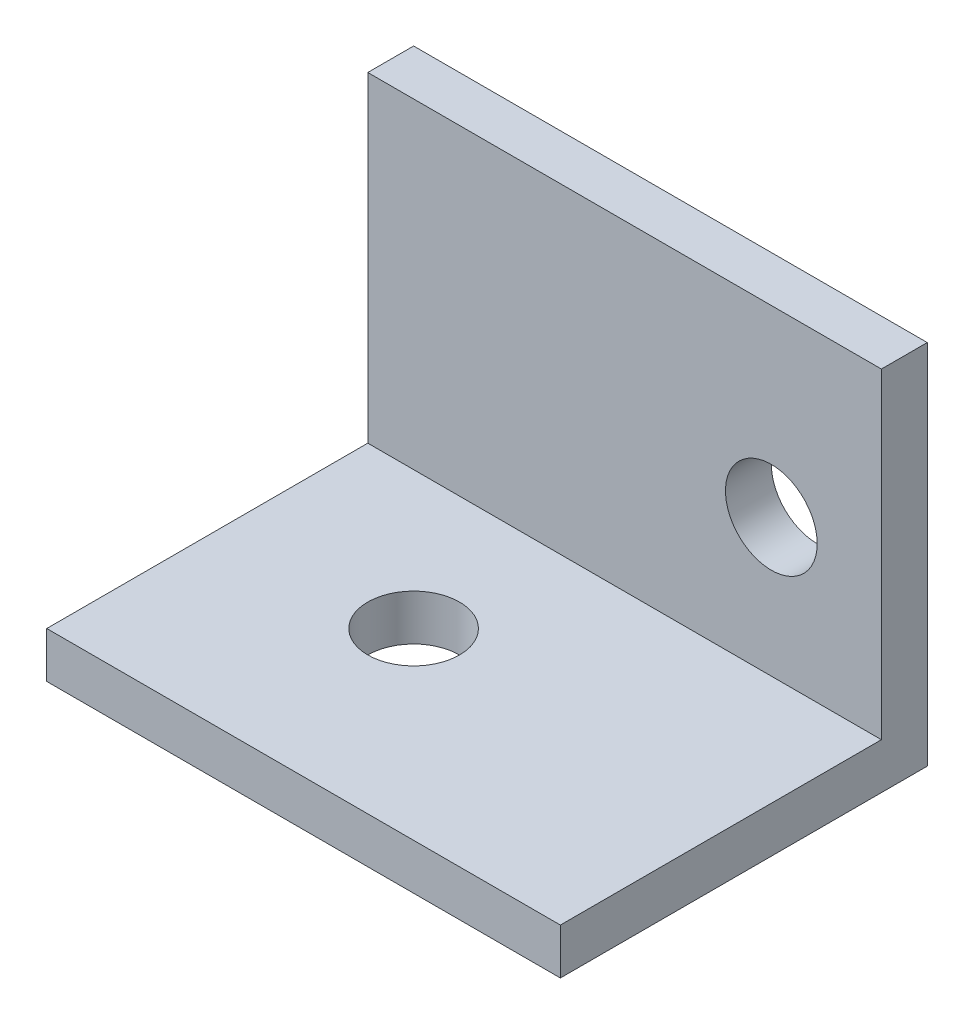
SolidWorks part; units mm, degrees
material "6061-T6 (SS)"
ref_plane "Front Plane" through (0, 0, 0) normal (0, 0, 1) x (1, 0, 0)
ref_plane "Top Plane" through (0, 0, 0) normal (0, 1, 0) x (1, 0, 0)
ref_plane "Right Plane" through (0, 0, 0) normal (1, 0, 0) x (0, 0, -1)
sketch "Sketch1" plane through (0, 0, 0) normal (0, 1, 0) x (1, 0, 0)
  line L1 (-17.78, -12.7) -> (17.78, -12.7)
  line L2 (-17.78, -12.7) -> (-17.78, 12.7)
  line L3 (-17.78, 12.7) -> (17.78, 12.7)
  line L4 (17.78, -12.7) -> (17.78, 12.7)
  line L5 (-17.78, -12.7) -> (17.78, 12.7) construction
  line L6 (-17.78, 12.7) -> (17.78, -12.7) construction
  point P0 (0, 0)
  dimension "D1" = 25.4
  dimension "D2" = 35.56
extrude "Boss-Extrude1" add sketch "Sketch1" along normal blind 3.175
sketch "Sketch2" plane through (0, 3.175, 0) normal (0, 1, 0) x (1, 0, 0)
  line L0 (17.78, -12.7) -> (17.78, 12.7) construction
  line L1 (-17.78, 12.7) -> (17.78, 12.7)
  line L2 (-17.78, 12.7) -> (-17.78, 9.525)
  line L3 (-17.78, 9.525) -> (17.78, 9.525)
  line L4 (17.78, 12.7) -> (17.78, 9.525)
  dimension "D1" = 3.175
extrude "Boss-Extrude2" add sketch "Sketch2" along normal blind 22.225
sketch "Sketch3" plane through (0, 3.175, 0) normal (0, 1, 0) x (1, 0, 0)
  line L0 (-17.78, 9.525) -> (-17.78, -12.7) construction
  line L1 (-17.78, -12.7) -> (17.78, -12.7) construction
  circle A0 centre (-5.08, 0) radius 3.175
  dimension "D1" = 6.35
  dimension "D2" = 12.7
  dimension "D3" = 12.7
extrude "Cut-Extrude1" cut sketch "Sketch3" against normal blind 3.175
sketch "Sketch4" plane through (0, 0, -9.525) normal (0, 0, 1) x (1, 0, 0)
  line L0 (17.78, 25.4) -> (17.78, 3.175) construction
  line L1 (-17.78, 25.4) -> (17.78, 25.4) construction
  circle A0 centre (10.16, 12.7) radius 3.175
  dimension "D1" = 6.35
  dimension "D2" = 7.62
  dimension "D3" = 12.7
extrude "Cut-Extrude2" cut sketch "Sketch4" against normal blind 3.175
